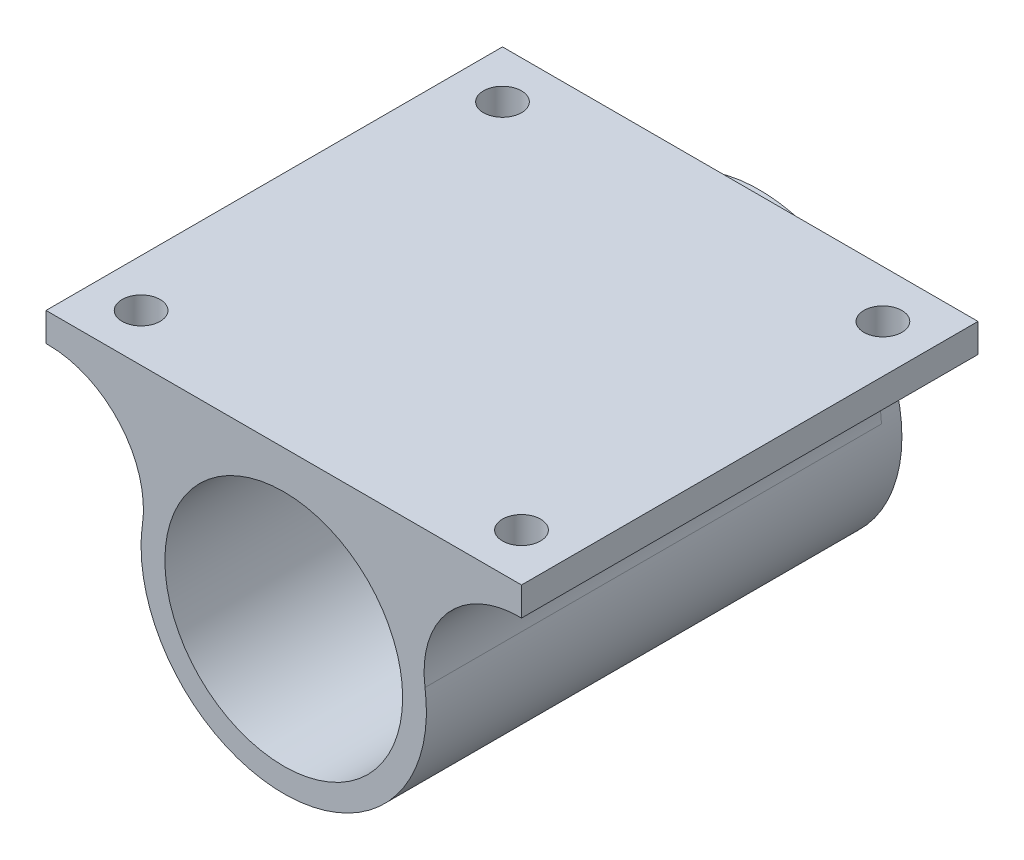
SolidWorks part; units mm, degrees
ref_plane "Front" through (0, 0, 0) normal (0, 0, 1) x (1, 0, 0)
ref_plane "Top" through (0, 0, 0) normal (0, 1, 0) x (1, 0, 0)
ref_plane "Right" through (0, 0, 0) normal (1, 0, 0) x (0, 0, -1)
sketch "Sketch1" plane through (0, 0, 0) normal (0, 0, 1) x (1, 0, 0)
  line L0 (24.7549, 13.4921) -> (25, 13.4921)
  line L1 (-25, 13.4921) -> (-24.7549, 13.4921)
  line L2 (-25, 13.4921) -> (-25, 16.5079)
  line L3 (-25, 16.5079) -> (25, 16.5079)
  line L4 (25, 13.4921) -> (25, 16.5079)
  circle A0 centre (0, 0) radius 12.5
  arc A1 (-14.8529, 2.0952) -> (14.8529, 2.0952) centre (0, 0) ccw
  arc A2 (24.7549, 13.4921) -> (14.8529, 2.0952) centre (24.7549, 3.4921) ccw
  arc A3 (-14.8529, 2.0952) -> (-24.7549, 13.4921) centre (-24.7549, 3.4921) ccw
  point P4 (0, 15)
  point P12 (6.5547, 13.4921)
  dimension "D1" = 25
  dimension "D2" = 30
  dimension "D4" = 10
  dimension "D3" = 50
extrude "Boss-Extrude1" add sketch "Sketch1" along normal blind 48 contours L3 L4 L0 A2 A1 A3 L1 L2
sketch "Sketch3" plane through (0, 0, 0) normal (0, 0, -1) x (-1, 0, 0)
  circle A0 centre (0, 0) radius 11
  circle A1 centre (0, 0) radius 15
  dimension "D1" = 22
  dimension "D2" = 30
extrude "Boss-Extrude3" add sketch "Sketch3" along normal blind 2
sketch "Sketch4" plane through (0, 16.5079, 0) normal (0, 1, 0) x (1, 0, 0)
  line L0 (25, -48) -> (25, 0) construction
  line L1 (25, 0) -> (-25, 0) construction
  line L2 (-25, -48) -> (-25, 0) construction
  line L3 (25, -48) -> (-25, -48) construction
  circle A0 centre (-20, -5) radius 2
  circle A1 centre (20, -5) radius 2
  circle A2 centre (20, -43) radius 2
  circle A3 centre (-20, -43) radius 2
  dimension "D1" = 4
  dimension "D2" = 4
  dimension "D3" = 4
  dimension "D4" = 4
  dimension "D5" = 5
  dimension "D6" = 5
  dimension "D7" = 5
  dimension "D8" = 5
  dimension "D9" = 5
  dimension "D10" = 5
  dimension "D11" = 5
  dimension "D12" = 5
extrude "Cut-Extrude1" cut sketch "Sketch4" against normal through all
